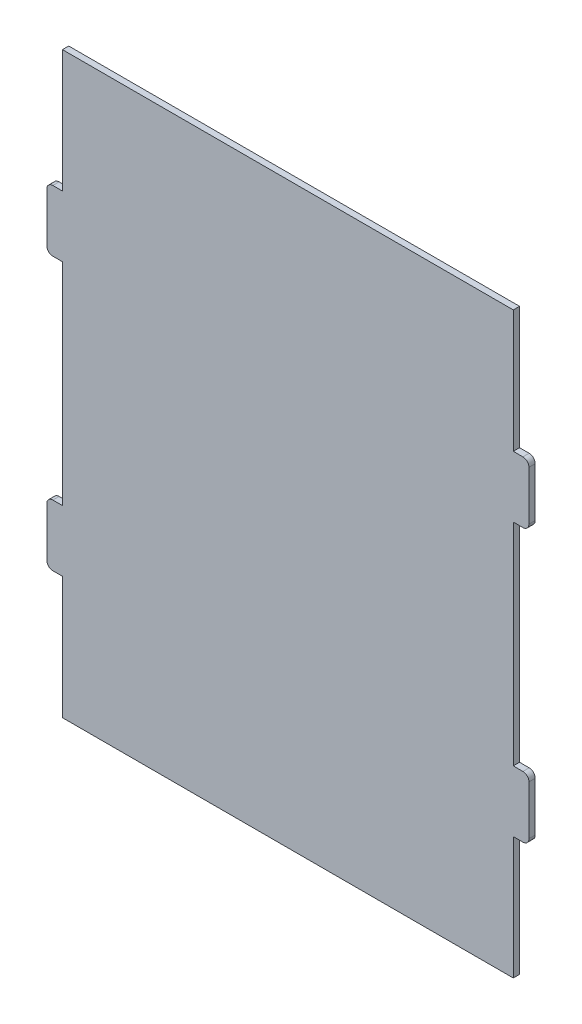
SolidWorks part; units mm, degrees
ref_plane "Front Plane" through (0, 0, 0) normal (0, 0, 1) x (1, 0, 0)
ref_plane "Top Plane" through (0, 0, 0) normal (0, 1, 0) x (1, 0, 0)
ref_plane "Right Plane" through (0, 0, 0) normal (1, 0, 0) x (0, 0, -1)
sketch "Model" plane through (0, 0, 0) normal (0, 0, 1) x (1, 0, 0)
  line L0 (-97.5, -43.8) -> (-93.5, -43.8)
  line L1 (-100, 46.3) -> (-100, 66.7)
  line L2 (-93.5, 120) -> (-93.5, 69.2)
  line L3 (93.5, 120) -> (-93.5, 120)
  line L4 (97.5, 69.2) -> (93.5, 69.2)
  line L5 (100, 46.3) -> (100, 66.7)
  line L6 (93.5, 43.8) -> (97.5, 43.8)
  line L7 (97.5, -43.8) -> (93.5, -43.8)
  line L8 (100, -66.7) -> (100, -46.3)
  line L9 (93.5, -69.2) -> (97.5, -69.2)
  line L10 (93.5, -120) -> (93.5, -69.2)
  line L11 (-93.5, -120) -> (93.5, -120)
  line L12 (-93.5, -69.2) -> (-93.5, -120)
  line L13 (-93.5, -69.2) -> (-97.5, -69.2)
  line L14 (-100, -66.7) -> (-100, -46.3)
  line L15 (93.5, -43.8) -> (93.5, 43.8)
  line L16 (93.5, 69.2) -> (93.5, 120)
  line L17 (-93.5, 43.8) -> (-97.5, 43.8)
  line L18 (-93.5, 43.8) -> (-93.5, -43.8)
  line L19 (-97.5, 69.2) -> (-93.5, 69.2)
  arc A0 (-97.5, -43.8) -> (-100, -46.3) centre (-97.5, -46.3) ccw
  arc A1 (-100, 46.3) -> (-97.5, 43.8) centre (-97.5, 46.3) ccw
  arc A2 (-97.5, 69.2) -> (-100, 66.7) centre (-97.5, 66.7) ccw
  arc A3 (100, 66.7) -> (97.5, 69.2) centre (97.5, 66.7) ccw
  arc A4 (97.5, 43.8) -> (100, 46.3) centre (97.5, 46.3) ccw
  arc A5 (100, -46.3) -> (97.5, -43.8) centre (97.5, -46.3) ccw
  arc A6 (97.5, -69.2) -> (100, -66.7) centre (97.5, -66.7) ccw
  arc A7 (-100, -66.7) -> (-97.5, -69.2) centre (-97.5, -66.7) ccw
extrude "Boss-Extrude1" add sketch "Model" along normal blind 2.6
